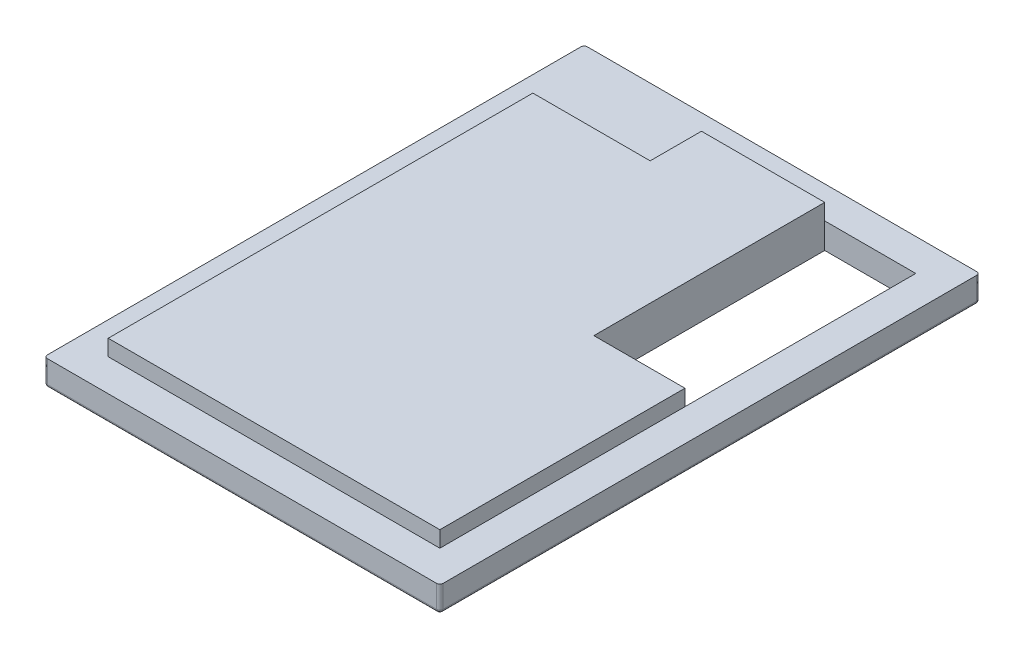
SolidWorks part; units mm, degrees
ref_plane "Front" through (0, 0, 0) normal (0, 0, 1) x (1, 0, 0)
ref_plane "Top" through (0, 0, 0) normal (0, 1, 0) x (1, 0, 0)
ref_plane "Right" through (0, 0, 0) normal (1, 0, 0) x (0, 0, -1)
sketch "Sketch1" plane through (0, 0, 0) normal (0, 1, 0) x (1, 0, 0)
  line L1 (-15.43, -21.055) -> (15.43, -21.055)
  line L2 (-15.43, -21.055) -> (-15.43, 21.055)
  line L3 (-15.43, 21.055) -> (15.43, 21.055)
  line L4 (15.43, -21.055) -> (15.43, 21.055)
  line L5 (-15.43, -21.055) -> (15.43, 21.055) construction
  line L6 (-15.43, 21.055) -> (15.43, -21.055) construction
  point P0 (0, 0)
  dimension "D1" = 30.86
  dimension "D2" = 42.11
extrude "Boss-Extrude1" add sketch "Sketch1" along normal blind 3.25
sketch "Sketch2" plane through (0, 3.25, 0) normal (0, 1, 0) x (1, 0, 0)
  line L8 (12.93, -18.555) -> (12.93, 18.555)
  line L9 (12.93, 18.555) -> (-12.93, 18.555)
  line L10 (-12.93, 18.555) -> (-12.93, -18.555)
  line L11 (-12.93, -18.555) -> (12.93, -18.555)
  line L12 (12.93, -18.555) -> (12.93, 18.555)
  line L13 (12.93, 18.555) -> (-12.93, 18.555)
  line L14 (-12.93, 18.555) -> (-12.93, -18.555)
  line L15 (-12.93, -18.555) -> (12.93, -18.555)
  dimension "D1" = 2.5
extrude "Cut-Extrude1" cut sketch "Sketch2" against normal blind 1.25 flip side to cut
fillet "Fillet1" radius 0.25 8 edges at (0, 0, -21.055) (-15.43, 1, -21.055) (-15.43, 0, 0) (15.43, 0, 0) (0, 0, 21.055) (-15.43, 1, 21.055) (15.43, 1, 21.055) (15.43, 1, -21.055)
sketch "Sketch4" plane through (0, 0, 0) normal (0, -1, 0) x (-1, 0, 0)
  line L0 (-15.43, 21.055) -> (15.18, 21.055) construction
  line L1 (-12.93, 18.555) -> (-5.83, 18.555)
  line L2 (-12.93, 18.555) -> (-12.93, 0.555)
  line L3 (-12.93, 0.555) -> (-5.83, 0.555)
  line L4 (-5.83, 18.555) -> (-5.83, 0.555)
  line L5 (-15.43, -20.805) -> (-15.43, 21.055) construction
  dimension "D1" = 2.5
  dimension "D2" = 2.5
  dimension "D3" = 7.1
  dimension "D4" = 18
extrude "Cut-Extrude3" cut sketch "Sketch4" against normal through all
sketch "Sketch5" plane through (0, 3.25, 0) normal (0, 1, 0) x (1, 0, 0)
  line L1 (-12.93, 18.555) -> (-3.78, 18.555)
  line L2 (-12.93, 18.555) -> (-12.93, 14.555)
  line L3 (-12.93, 14.555) -> (-3.78, 14.555)
  line L4 (-3.78, 18.555) -> (-3.78, 14.555)
  dimension "D1" = 9.15
  dimension "D2" = 4
extrude "Cut-Extrude4" cut sketch "Sketch5" against normal blind 1.25
